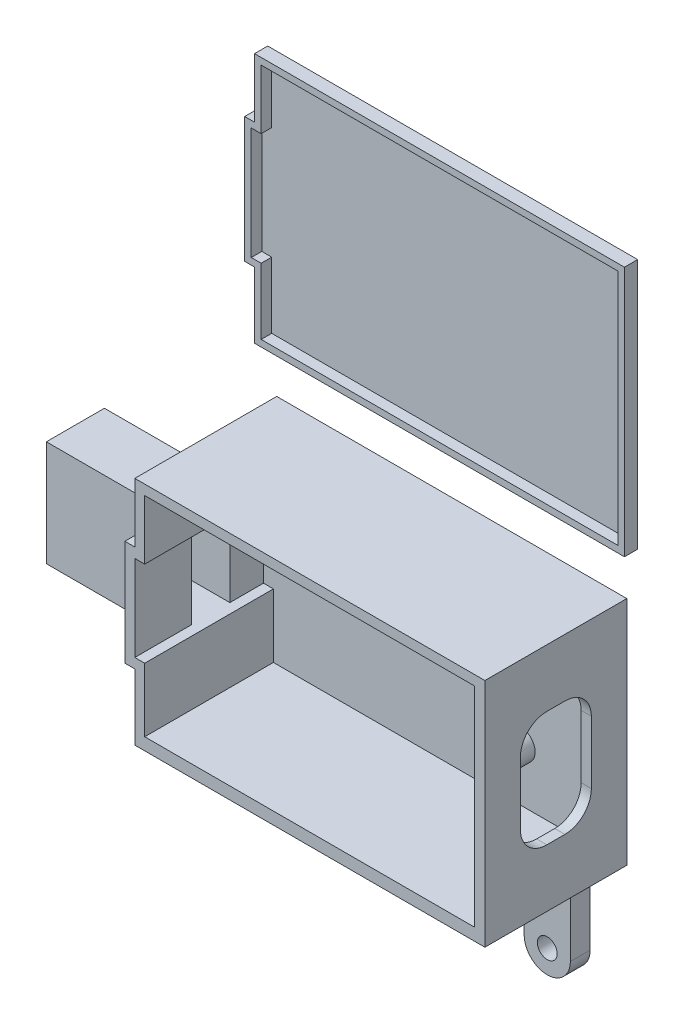
SolidWorks part; units mm, degrees
ref_plane "Alzado" through (0, 0, 0) normal (0, 0, 1) x (1, 0, 0)
ref_plane "Planta" through (0, 0, 0) normal (0, 1, 0) x (1, 0, 0)
ref_plane "Vista lateral" through (0, 0, 0) normal (1, 0, 0) x (0, 0, -1)
sketch "Croquis1" plane through (0, 0, 0) normal (0, 0, 1) x (1, 0, 0)
  line L1 (0, 0) -> (50, 0)
  line L2 (0, 0) -> (0, 5)
  line L3 (0, 27) -> (50, 27)
  line L4 (50, 0) -> (50, 27)
  line L6 (-1.5, -6.5) -> (-1.5, 3.5)
  line L8 (-22, 18) -> (-22, 19.5)
  line L9 (-1.5, 28.5) -> (51.5388, 28.5)
  line L10 (-1.5, 28.5) -> (-1.5, 19.5)
  line L13 (-22, 18) -> (0, 18)
  line L14 (-22, 18) -> (-22, 5)
  line L15 (-22, 5) -> (0, 5)
  line L16 (0, 18) -> (0, 27)
  line L18 (-22, 19.5) -> (-1.5, 19.5)
  line L19 (-22, 5) -> (-22, 3.5)
  line L20 (-22, 3.5) -> (-1.5, 3.5)
  line L21 (51.5388, 28.5) -> (51.5388, -6.5)
  line L22 (51.5388, -6.5) -> (-1.5, -6.5)
extrude "Saliente-Extruir1" add sketch "Croquis1" along normal blind 23 contours L22 L21 L9 L10 L18 L8 L13 L16 L3 L4 L1 L2 L15 L19 L20 L6
sketch "Croquis2" plane through (0, 0, 0) normal (0, 0, -1) x (-1, 0, 0)
  line L1 (-51.5388, 28.5) -> (1.5, 28.5)
  line L2 (-51.5388, 28.5) -> (-51.5388, -6.5)
  line L3 (-51.5388, -6.5) -> (1.5, -6.5)
  line L4 (1.5, 28.5) -> (1.5, -6.5)
extrude "Saliente-Extruir2" add sketch "Croquis2" along normal blind 1.5
sketch "Croquis3" plane through (0, 3.5, 0) normal (0, -1, 0) x (1, 0, 0)
  line L1 (-22, 23) -> (-22, 0) construction
  line L2 (-1.5, 23) -> (-1.5, 0) construction
  line L3 (-22, 14.4) -> (-1.5, 14.4)
  line L4 (-22, 8.6) -> (-1.5, 8.6)
  line L5 (-22, 23) -> (-1.5, 23) construction
  line L6 (-22, 14.4) -> (-1.5, 14.4)
  line L7 (-22, 14.4) -> (-22, 23)
  line L8 (-22, 23) -> (-1.5, 23)
  line L11 (-1.5, 14.4) -> (-1.5, 23)
  line L17 (-22, 8.6) -> (-1.5, 8.6)
  line L18 (-22, 8.6) -> (-22, 0)
  line L19 (-22, 0) -> (-1.5, 0)
  line L20 (-1.5, 8.6) -> (-1.5, 0)
  line M13 (-22, 0) -> (-1.5, 0)
  line M14 (-1.5, 0) -> (-1.5, 23)
  line M15 (-1.5, 23) -> (-22, 23)
  line M16 (-22, 23) -> (-22, 0)
extrude "Cortar-Extruir1" cut sketch "Croquis3" against normal up to surface (16 mm away) contours L3 M16 M14 M15 | L4 M16 M13 M14 up to face at (-11.75, 19.5, 11.5)
sketch "Croquis4" plane through (0, 3.5, 0) normal (0, -1, 0) x (1, 0, 0)
  line L1 (-22, 14.4) -> (-1.5, 14.4)
  line L2 (-22, 14.4) -> (-22, 15.9)
  line L3 (-22, 15.9) -> (-3, 15.9)
  line L5 (-22, 8.6) -> (-1.5, 8.6)
  line L6 (-22, 8.6) -> (-22, 7.1)
  line L7 (-22, 7.1) -> (-3, 7.1)
  line L11 (-3, 7.1) -> (-3, -1.5)
  line L12 (-3, -1.5) -> (-1.5, -1.5)
  line L13 (-1.5, 8.6) -> (-1.5, -1.5)
  line L16 (-3, 15.9) -> (-3, 23)
  line L17 (-3, 23) -> (-1.5, 23)
  line L18 (-1.5, 14.4) -> (-1.5, 23)
extrude "Saliente-Extruir4" add sketch "Croquis4" against normal up to surface (16 mm away) up to face at (-11.75, 19.5, 11.5)
sketch "Agujeros" plane through (0, 0, 0) normal (0, 0, 1) x (1, 0, 0)
  circle A0 centre (37.4, 3.4) radius 1.5
  circle A1 centre (7.3, 18.8) radius 1.5
sketch "Croquis12" plane through (0, -6.5, 0) normal (0, -1, 0) x (1, 0, 0)
  line L1 (-3, -1.5) -> (46.5, -1.5)
  line L2 (-3, -1.5) -> (-3, 3.5)
  line L3 (-3, 3.5) -> (46.5, 3.5)
  line L4 (46.5, -1.5) -> (46.5, 3.5)
extrude "Cortar-Extruir5" cut sketch "Croquis12" against normal up to surface (35 mm away) up to face at (25.0194, 28.5, 10.75)
sketch "Croquis14" plane through (0, 0, 3.5) normal (0, 0, -1) x (-1, 0, 0)
  line L0 (1.5, 3.5) -> (1.5, -6.5)
  line L1 (-51.5388, 28.5) -> (1.5, 28.5)
  line L2 (-51.5388, 28.5) -> (-51.5388, -6.5)
  line L3 (-51.5388, -6.5) -> (1.5, -6.5)
  line L4 (1.5, 28.5) -> (1.5, 19.5)
  line L5 (1.5, 19.5) -> (3, 19.5)
  line L7 (1.5, 3.5) -> (3, 3.5)
  line L8 (3, 19.5) -> (3, 3.5)
sketch "Croquis27" plane through (0, 0, 23) normal (0, 0, 1) x (1, 0, 0)
  line L0 (0, 0) -> (50, 0) construction
  line L1 (0, 0) -> (50, 0)
  line L2 (0, 0) -> (0, -4.6529)
  line L3 (0, -4.6529) -> (50, -4.6529)
  line L4 (50, 0) -> (50, -4.6529)
extrude "Saliente-Extruir14" add sketch "Croquis14" along normal blind 2
extrude "Cortar-Extruir12" cut sketch "Agujeros" along normal up to surface (3.5 mm away) up to face at (12.125, 12.5, 3.5)
sketch "Croquis29" plane through (0, 0, 3.5) normal (0, 0, 1) x (1, 0, 0)
  circle A0 centre (7.3, 18.8) radius 1.5
  circle A1 centre (7.3, 18.8) radius 2.2983
  circle A2 centre (37.4, 3.4) radius 2.25
  circle A3 centre (37.4, 3.4) radius 1.5
extrude "Saliente-Extruir15" add sketch "Croquis29" along normal blind 3.5
extrude "Cortar-Extruir15" cut sketch "Croquis27" against normal blind 19.5
sketch "Croquis30" plane through (46.5, 0, 0) normal (-1, 0, 0) x (0, 0, 1)
  line L1 (1.5, 28.5) -> (-1.5, 28.5)
  line L2 (1.5, 28.5) -> (1.5, -6.5)
  line L3 (1.5, -6.5) -> (-1.5, -6.5)
  line L4 (-1.5, 28.5) -> (-1.5, -6.5)
extrude "Cortar-Extruir17" cut sketch "Croquis30" against normal up to surface (5.0388 mm away) up to face at (51.5388, 11, 10.75)
sketch "Croquis31" plane through (0, 0, 1.5) normal (0, 0, -1) x (-1, 0, 0)
  line L13 (2.8581, 45.7972) -> (4.3581, 45.7972)
  line L14 (-53.1807, 35.7972) -> (2.8581, 35.7972)
  line L15 (-53.1807, 35.7972) -> (-53.1807, 73.7972)
  line L16 (-53.1807, 73.7972) -> (2.8581, 73.7972)
  line L17 (2.8581, 35.7972) -> (2.8581, 45.7972)
  line L18 (2.8581, 64.7972) -> (2.8581, 73.7972)
  line L19 (2.8581, 64.7972) -> (4.3581, 64.7972)
  line L21 (2.8581, 45.7972) -> (4.3581, 45.7972)
  line L22 (4.3581, 64.7972) -> (4.3581, 45.7972)
extrude "Saliente-Extruir16" add sketch "Croquis31" against normal blind 2 separate body contours L22 L19 L18 L16 L15 L14 L17 L13
sketch "Croquis32" plane through (0, 0, 3.5) normal (0, 0, 1) x (1, 0, 0)
  line L0 (-1.8581, 46.7972) -> (-1.8581, 36.7972)
  line L1 (52.1807, 72.7972) -> (-1.8581, 72.7972)
  line L2 (52.1807, 72.7972) -> (52.1807, 36.7972)
  line L3 (52.1807, 36.7972) -> (-1.8581, 36.7972)
  line L4 (-1.8581, 72.7972) -> (-1.8581, 63.7972)
  line L5 (-3.3581, 63.7972) -> (-1.8581, 63.7972)
  line L6 (-3.3581, 63.7972) -> (-3.3581, 46.7972)
  line L7 (-3.3581, 46.7972) -> (-1.8581, 46.7972)
  line L8 (53.1807, 35.7972) -> (53.1807, 73.7972) construction
  line L9 (53.1807, 73.7972) -> (-2.8581, 73.7972) construction
  line L10 (-2.8581, 64.7972) -> (-2.8581, 73.7972) construction
  line L11 (-4.3581, 64.7972) -> (-4.3581, 45.7972) construction
  line L12 (-2.8581, 64.7972) -> (-4.3581, 64.7972) construction
  line L13 (53.1807, 35.7972) -> (-2.8581, 35.7972) construction
  line L14 (-2.8581, 45.7972) -> (-4.3581, 45.7972) construction
  dimension "D1" = 1
  dimension "D2" = 1
  dimension "D3" = 1
  dimension "D4" = 1
  dimension "D5" = 1
  dimension "D6" = 1
  dimension "D7" = 1
extrude "Cortar-Extruir19" cut sketch "Croquis32" against normal blind 1.6
sketch "Croquis34" plane through (51.5388, 0, 0) normal (1, 0, 0) x (0, 0, -1)
  line L1 (-13.625, 19.75) -> (-10.875, 19.75)
  line L2 (-17.625, 15.75) -> (-17.625, 6.25)
  line L3 (-13.625, 2.25) -> (-10.875, 2.25)
  line L4 (-6.875, 15.75) -> (-6.875, 6.25)
  arc A0 (-17.625, 6.25) -> (-13.625, 2.25) centre (-13.625, 6.25) ccw
  arc A1 (-10.875, 2.25) -> (-6.875, 6.25) centre (-10.875, 6.25) ccw
  arc A2 (-10.875, 19.75) -> (-6.875, 15.75) centre (-10.875, 15.75) cw
  arc A3 (-13.625, 19.75) -> (-17.625, 15.75) centre (-13.625, 15.75) ccw
  dimension "D1" = 4
extrude "Cortar-Extruir20" cut sketch "Croquis34" against normal up to surface (1.5388 mm away) up to face at (50, 11.1736, 13.25)
sketch "Croquis35" plane through (0, 0, 1.5) normal (0, 0, -1) x (-1, 0, 0)
  line L0 (-42.487, -6.5) -> (-42.487, -20.3966) construction
  line L1 (-51.5388, -6.5) -> (1.5, -6.5) construction
  line L2 (-38.987, -6.5) -> (-38.987, -20.3966)
  line L3 (-45.987, -6.5) -> (-45.987, -20.3966)
  line L4 (-7.7331, -6.5) -> (-7.7331, -20.3966) construction
  line L5 (-4.2331, -6.5) -> (-4.2331, -20.3966)
  line L6 (-11.2331, -6.5) -> (-11.2331, -20.3966)
  line L7 (-45.987, -6.5) -> (-38.987, -6.5)
  line L8 (-11.2331, -6.5) -> (-4.2331, -6.5)
  arc A1 (-45.987, -20.3966) -> (-38.987, -20.3966) centre (-42.487, -20.3966) ccw
  circle A2 centre (-42.487, -20.3966) radius 1.5
  arc A4 (-11.2331, -20.3966) -> (-4.2331, -20.3966) centre (-7.7331, -20.3966) ccw
  circle A5 centre (-7.7331, -20.3966) radius 1.5
  point P4 (-42.487, -13.4483)
  point P13 (-7.7331, -13.4483)
extrude "Saliente-Extruir17" add sketch "Croquis35" against normal blind 3
